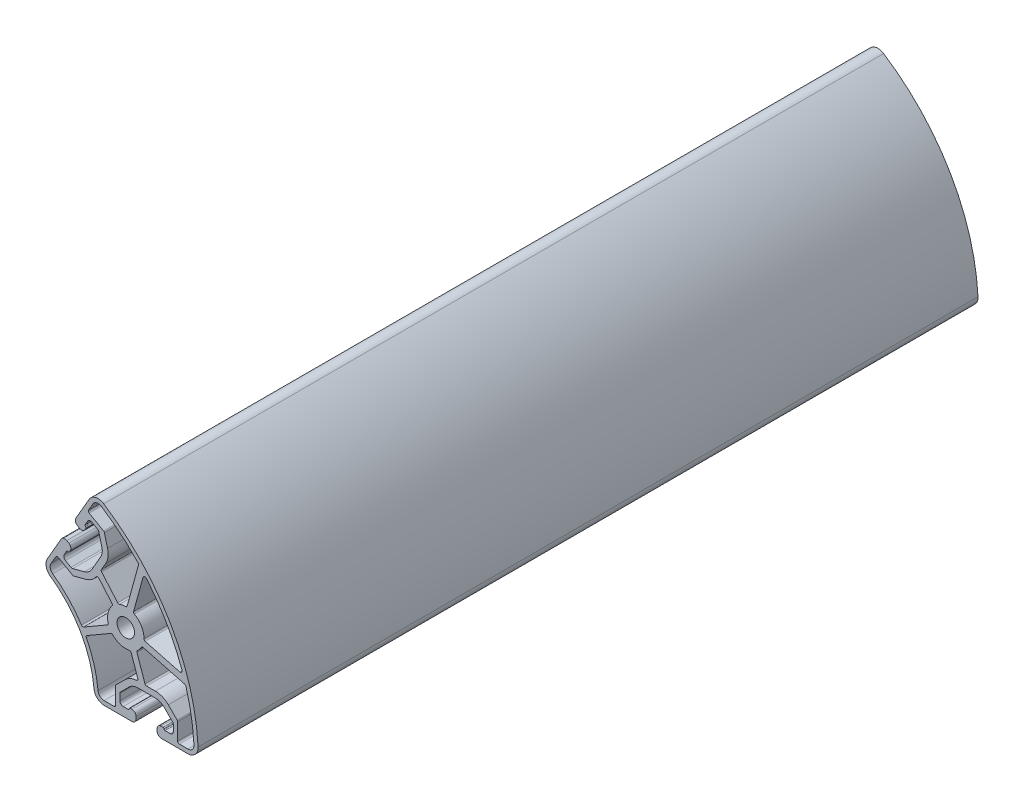
SolidWorks part; units mm, degrees
material "6105-T5 Aluminum"
ref_plane "Front Plane" through (0, 0, 0) normal (0, 0, 1) x (1, 0, 0)
ref_plane "Top Plane" through (0, 0, 0) normal (0, 1, 0) x (1, 0, 0)
ref_plane "Right Plane" through (0, 0, 0) normal (1, 0, 0) x (0, 0, -1)
sketch "Sketch1" plane through (0, 0, 0) normal (0, 0, 1) x (1, 0, 0)
  line L0 (4.8853, 23.3078) -> (0.539, 7.4661)
  line L1 (-3.1026, 6.7541) -> (-9.3079, 13.9221)
  line L2 (-9.3777, 14.6553) -> (-7.6892, 17.58)
  line L3 (-6.9859, 22.9219) -> (-8.2275, 27.5555)
  line L4 (-8.5247, 27.9429) -> (-14.0551, 31.1359)
  line L5 (-14.2909, 31.9974) -> (-12.6703, 34.875)
  line L6 (20.7474, -4.3348) -> (7.4703, -0.8367)
  line L7 (3.0139, 6.8865) -> (6.6419, 20.1104)
  line L8 (-19.9786, 7.2019) -> (-15.3291, 8.4478)
  line L9 (-10.3434, 11.3324) -> (-5.2755, 5.4271)
  line L10 (-7.0377, -2.5975) -> (-16.187, -7.8797)
  line L11 (-28.7595, 7.0169) -> (-26.8571, 10.2321)
  line L12 (-25.9931, 10.4587) -> (-20.4627, 7.2657)
  line L13 (2.0629, -7.2835) -> (4.6432, -14.6255)
  line L14 (-0.3284, -17.4994) -> (-3.7321, -20.9031)
  line L15 (-3.919, -21.3543) -> (-3.919, -27.833)
  line L16 (-4.554, -28.468) -> (-8.3232, -28.468)
  line L17 (-14.917, -10.0795) -> (-5.7677, -4.7972)
  line L18 (7.4032, -15.0221) -> (4.2986, -6.0652)
  line L19 (6.7358, -3.2699) -> (22.6399, -7.4601)
  line L20 (23.8956, -28.468) -> (20.592, -28.468)
  line L21 (19.957, -27.833) -> (19.957, -21.3543)
  line L22 (19.7702, -20.9031) -> (16.3781, -17.5111)
  line L23 (11.4002, -15.4492) -> (8.0031, -15.4492)
  line L24 (13.5936, -30.058) -> (23.8323, -30.058)
  line L25 (-14.1148, 35.6684) -> (-19.2342, 26.8014)
  line L26 (-18.6184, 24.701) -> (-17.8266, 24.2438)
  line L27 (-15.7151, 24.7696) -> (-15.3301, 25.4365)
  line L28 (-15.4578, 25.9486) -> (-15.482, 25.9638)
  line L29 (-15.6097, 26.476) -> (-14.6543, 28.1308)
  line L30 (-12.9197, 28.5956) -> (-10.8065, 27.3756)
  line L31 (-10.3923, 26.8358) -> (-9.1894, 22.3466)
  line L32 (-9.6639, 18.7428) -> (-13.0446, 12.8871)
  line L33 (-15.9284, 10.6743) -> (-20.4177, 9.4714)
  line L34 (-21.0922, 9.5602) -> (-23.2053, 10.7802)
  line L35 (-23.6701, 12.5149) -> (-22.7147, 14.1697)
  line L36 (-22.2073, 14.3152) -> (-22.1821, 14.3018)
  line L37 (-21.6747, 14.4473) -> (-21.3214, 15.0591)
  line L38 (-21.8978, 17.2101) -> (-22.6896, 17.6672)
  line L39 (-24.8405, 17.0909) -> (-30.1429, 7.9069)
  line L40 (-8.2238, -30.058) -> (2.3809, -30.058)
  line L41 (3.9555, -28.4834) -> (3.9555, -27.5691)
  line L42 (2.3809, -25.9945) -> (1.6745, -25.9945)
  line L43 (1.2947, -26.3612) -> (1.2937, -26.3897)
  line L44 (0.914, -26.7564) -> (-0.9968, -26.7564)
  line L45 (-2.2667, -25.4865) -> (-2.2667, -23.0464)
  line L46 (-2.0063, -22.4179) -> (1.2801, -19.1315)
  line L47 (4.6383, -17.7405) -> (11.3998, -17.7405)
  line L48 (14.758, -19.1315) -> (18.0444, -22.4179)
  line L49 (18.3048, -23.0464) -> (18.3048, -25.4865)
  line L50 (17.0349, -26.7564) -> (15.124, -26.7564)
  line L51 (14.7443, -26.3897) -> (14.7433, -26.3612)
  line L52 (14.3636, -25.9945) -> (13.5936, -25.9945)
  line L53 (12.0825, -27.5602) -> (12.0825, -28.4745)
  arc A0 (-9.3424, 35.6924) -> (-12.6703, 34.875) centre (-10.6227, 33.7218) ccw
  arc A1 (4.7026, 24.0332) -> (-9.3424, 35.6924) centre (-52.0623, -30.0582) ccw
  arc A2 (4.8853, 23.3078) -> (4.7026, 24.0332) centre (4.1524, 23.5089) ccw
  arc A3 (-0.0672, 6.9991) -> (0.539, 7.4661) centre (-0.0733, 7.6341) ccw
  arc A4 (-0.0672, 6.9991) -> (-2.4044, 6.5734) centre (0.0003, -0.0006) ccw
  arc A5 (-3.1026, 6.7541) -> (-2.4044, 6.5734) centre (-2.6225, 7.1698) ccw
  arc A6 (-9.3777, 14.6553) -> (-9.3079, 13.9221) centre (-8.8278, 14.3378) ccw
  arc A7 (-7.6892, 17.58) -> (-6.9859, 22.9219) centre (-13.7858, 21.0999) ccw
  arc A8 (-8.2275, 27.5555) -> (-8.5247, 27.9429) centre (-8.8437, 27.3904) ccw
  arc A9 (-14.2909, 31.9974) -> (-14.0551, 31.1359) centre (-13.7376, 31.6858) ccw
  arc A10 (7.9566, 20.3984) -> (6.6419, 20.1104) centre (7.3748, 19.9093) ccw
  arc A11 (21.6555, -3.3409) -> (7.9566, 20.3984) centre (-52.0623, -30.0582) ccw
  arc A12 (20.7474, -4.3348) -> (21.6555, -3.3409) centre (20.941, -3.5999) ccw
  arc A13 (6.9974, -0.2042) -> (7.4703, -0.8367) centre (7.6321, -0.2227) ccw
  arc A14 (6.9974, -0.2042) -> (3.3247, 6.1597) centre (0.0003, -0.0006) ccw
  arc A15 (3.0139, 6.8865) -> (3.3247, 6.1597) centre (3.6263, 6.7185) ccw
  arc A16 (-20.4627, 7.2657) -> (-19.9786, 7.2019) centre (-20.1437, 7.8182) ccw
  arc A17 (-15.3291, 8.4478) -> (-11.3505, 11.2757) centre (-17.1408, 15.2093) ccw
  arc A18 (-10.3434, 11.3324) -> (-11.3505, 11.2757) centre (-10.8253, 10.9189) ccw
  arc A19 (-5.2785, 4.5966) -> (-5.2755, 5.4271) centre (-5.7574, 5.0136) ccw
  arc A20 (-5.2785, 4.5966) -> (-6.7434, -1.8773) centre (0.0003, -0.0006) ccw
  arc A21 (-7.0377, -2.5975) -> (-6.7434, -1.8773) centre (-7.3552, -2.0475) ccw
  arc A22 (-17.0395, -7.6718) -> (-16.187, -7.8797) centre (-16.5045, -7.3298) ccw
  arc A23 (-17.0395, -7.6718) -> (-28.0922, 3.9004) centre (-52.0623, -30.0582) ccw
  arc A24 (-28.7595, 7.0169) -> (-28.0922, 3.9004) centre (-26.737, 5.8203) ccw
  arc A25 (-25.9931, 10.4587) -> (-26.8571, 10.2321) centre (-26.3106, 9.9087) ccw
  arc A26 (2.0629, -7.2835) -> (1.3421, -6.8708) centre (1.4638, -7.494) ccw
  arc A27 (4.0921, -15.4692) -> (4.6432, -14.6255) centre (4.0441, -14.836) ccw
  arc A28 (4.0921, -15.4692) -> (-0.3284, -17.4994) centre (4.6214, -22.4492) ccw
  arc A29 (-3.7321, -20.9031) -> (-3.919, -21.3543) centre (-3.281, -21.3543) ccw
  arc A30 (-4.554, -28.468) -> (-3.919, -27.833) centre (-4.554, -27.833) ccw
  arc A31 (-10.6638, -26.3288) -> (-8.3232, -28.468) centre (-8.3232, -26.118) ccw
  arc A32 (-10.6638, -26.3288) -> (-15.1632, -10.9217) centre (-52.0623, -30.0582) ccw
  arc A33 (-14.917, -10.0795) -> (-15.1632, -10.9217) centre (-14.5995, -10.6294) ccw
  arc A34 (-4.9969, -4.9024) -> (-5.7677, -4.7972) centre (-5.4502, -5.3471) ccw
  arc A35 (-4.9969, -4.9024) -> (1.3421, -6.8708) centre (0.0003, -0.0006) ccw
  arc A36 (4.4912, -5.3702) -> (4.2986, -6.0652) centre (4.8985, -5.8573) ccw
  arc A37 (4.4912, -5.3702) -> (6.0273, -3.5609) centre (0.0003, -0.0006) ccw
  arc A38 (6.7358, -3.2699) -> (6.0273, -3.5609) centre (6.574, -3.8839) ccw
  arc A39 (23.1755, -7.981) -> (22.6399, -7.4601) centre (22.4462, -8.195) ccw
  arc A40 (26.2424, -25.9962) -> (23.1755, -7.981) centre (-52.0623, -30.0582) ccw
  arc A41 (23.8956, -28.468) -> (26.2424, -25.9962) centre (23.8956, -26.118) ccw
  arc A42 (19.957, -27.833) -> (20.592, -28.468) centre (20.592, -27.833) ccw
  arc A43 (19.957, -21.3543) -> (19.7702, -20.9031) centre (19.319, -21.3543) ccw
  arc A44 (16.3781, -17.5111) -> (11.4002, -15.4492) centre (11.4002, -22.489) ccw
  arc A45 (7.4032, -15.0221) -> (8.0031, -15.4492) centre (8.0031, -14.8142) ccw
  circle A46 centre (0, 0) radius 3.3782
  arc A47 (23.8323, -30.058) -> (27.8268, -25.8474) centre (23.8323, -26.058) ccw
  arc A48 (27.8268, -25.8474) -> (-8.4712, 37.0225) centre (-52.0623, -30.0582) ccw
  arc A49 (-8.4712, 37.0225) -> (-14.1148, 35.6684) centre (-10.6507, 33.6684) ccw
  arc A50 (-19.2342, 26.8014) -> (-18.6184, 24.701) centre (-17.815, 26.077) ccw
  arc A51 (-17.8266, 24.2438) -> (-15.7151, 24.7696) centre (-17.0413, 25.5926) ccw
  arc A52 (-15.3301, 25.4365) -> (-15.4578, 25.9486) centre (-15.6592, 25.6264) ccw
  arc A53 (-15.6097, 26.476) -> (-15.482, 25.9638) centre (-15.2807, 26.286) ccw
  arc A54 (-12.9197, 28.5956) -> (-14.6543, 28.1308) centre (-13.5546, 27.4959) ccw
  arc A55 (-10.3923, 26.8358) -> (-10.8065, 27.3756) centre (-11.2509, 26.6058) ccw
  arc A56 (-9.6639, 18.7428) -> (-9.1894, 22.3466) centre (-13.7768, 21.1174) ccw
  arc A57 (-15.9284, 10.6743) -> (-13.0446, 12.8871) centre (-17.1576, 15.2617) ccw
  arc A58 (-21.0922, 9.5602) -> (-20.4177, 9.4714) centre (-20.6477, 10.33) ccw
  arc A59 (-23.6701, 12.5149) -> (-23.2053, 10.7802) centre (-22.5704, 11.8799) ccw
  arc A60 (-22.2073, 14.3152) -> (-22.7147, 14.1697) centre (-22.3857, 13.9797) ccw
  arc A61 (-22.1821, 14.3018) -> (-21.6747, 14.4473) centre (-22.0037, 14.6373) ccw
  arc A62 (-21.3214, 15.0591) -> (-21.8978, 17.2101) centre (-22.6851, 15.8464) ccw
  arc A63 (-22.6896, 17.6672) -> (-24.8405, 17.0909) centre (-23.4769, 16.3036) ccw
  arc A64 (-30.1429, 7.9069) -> (-28.9846, 2.6383) centre (-26.6788, 5.9069) ccw
  arc A65 (-12.2074, -26.4206) -> (-28.9846, 2.6383) centre (-52.0426, -30.0469) ccw
  arc A66 (-12.2074, -26.4206) -> (-8.2238, -30.058) centre (-8.2238, -26.058) ccw
  arc A67 (2.3809, -30.058) -> (3.9555, -28.4834) centre (2.3809, -28.4834) ccw
  arc A68 (3.9555, -27.5691) -> (2.3809, -25.9945) centre (2.3809, -27.5691) ccw
  arc A69 (1.6745, -25.9945) -> (1.2947, -26.3612) centre (1.6745, -26.3744) ccw
  arc A70 (0.914, -26.7564) -> (1.2937, -26.3897) centre (0.914, -26.3764) ccw
  arc A71 (-2.2667, -25.4865) -> (-0.9968, -26.7564) centre (-0.9968, -25.4865) ccw
  arc A72 (-2.0063, -22.4179) -> (-2.2667, -23.0464) centre (-1.3778, -23.0464) ccw
  arc A73 (4.6383, -17.7405) -> (1.2801, -19.1315) centre (4.6383, -22.4897) ccw
  arc A74 (14.758, -19.1315) -> (11.3998, -17.7405) centre (11.3998, -22.4897) ccw
  arc A75 (18.3048, -23.0464) -> (18.0444, -22.4179) centre (17.4159, -23.0464) ccw
  arc A76 (17.0349, -26.7564) -> (18.3048, -25.4865) centre (17.0349, -25.4865) ccw
  arc A77 (14.7443, -26.3897) -> (15.124, -26.7564) centre (15.124, -26.3764) ccw
  arc A78 (14.7433, -26.3612) -> (14.3636, -25.9945) centre (14.3636, -26.3744) ccw
  arc A79 (13.5936, -25.9945) -> (12.0825, -27.5602) centre (13.6433, -27.5544) ccw
  arc A80 (12.0825, -28.4745) -> (13.5936, -30.058) centre (13.6759, -28.4667) ccw
extrude "Extrude1" add sketch "Sketch1" against normal blind 300
